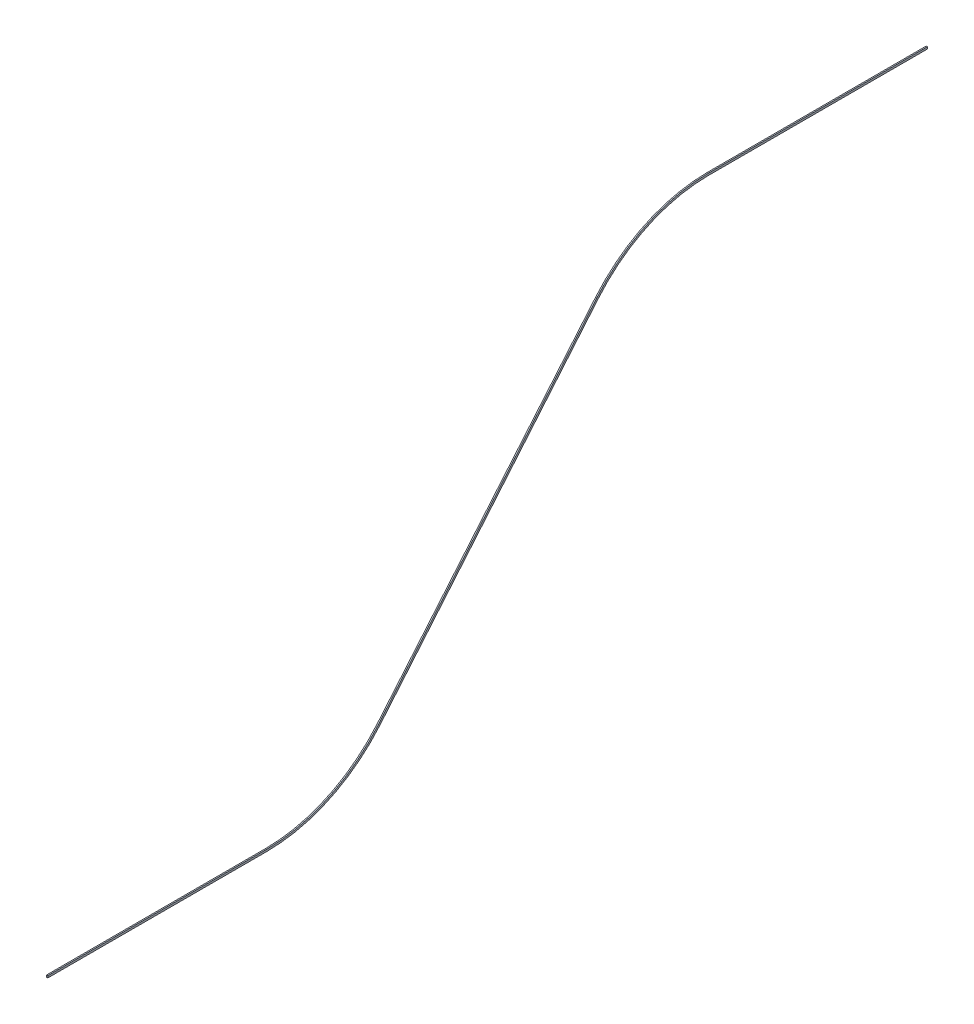
SolidWorks part; units mm, degrees
ref_plane "Front Plane" through (0, 0, 0) normal (0, 0, 1) x (1, 0, 0)
ref_plane "Top Plane" through (0, 0, 0) normal (0, 1, 0) x (1, 0, 0)
ref_plane "Right Plane" through (0, 0, 0) normal (1, 0, 0) x (0, 0, -1)
sketch "Sketch1" plane through (0, 0, 0) normal (1, 0, 0) x (0, 0, -1)
  line L0 (0, 0) -> (600, 0)
  line L1 (906.4178, 142.885) -> (1505.728, 857.115)
  line L2 (1812.1458, 1000) -> (2412.1458, 1000)
  line L3 (0, -5.5) -> (600, -5.5)
  line L4 (910.631, 139.3496) -> (1509.9412, 853.5797)
  line L5 (1812.1458, 994.5) -> (2412.1458, 994.5)
  line L6 (2412.1458, 994.5) -> (2412.1458, 1000)
  line L7 (0, 0) -> (0, -5.5)
  arc A0 (600, 0) -> (906.4178, 142.885) centre (600, 400) ccw
  arc A1 (1505.728, 857.115) -> (1812.1458, 1000) centre (1812.1458, 600) cw
  arc A2 (600, -5.5) -> (910.631, 139.3496) centre (600, 400) ccw
  arc A3 (1509.9412, 853.5797) -> (1812.1458, 994.5) centre (1812.1458, 600) cw
  dimension "D4" = 1000
  dimension "D1" = 600
  dimension "D2" = 400
  dimension "D3" = 50
  dimension "D5" = 5.5
extrude "Boss-Extrude1" add sketch "Sketch1" along normal blind 3.4
